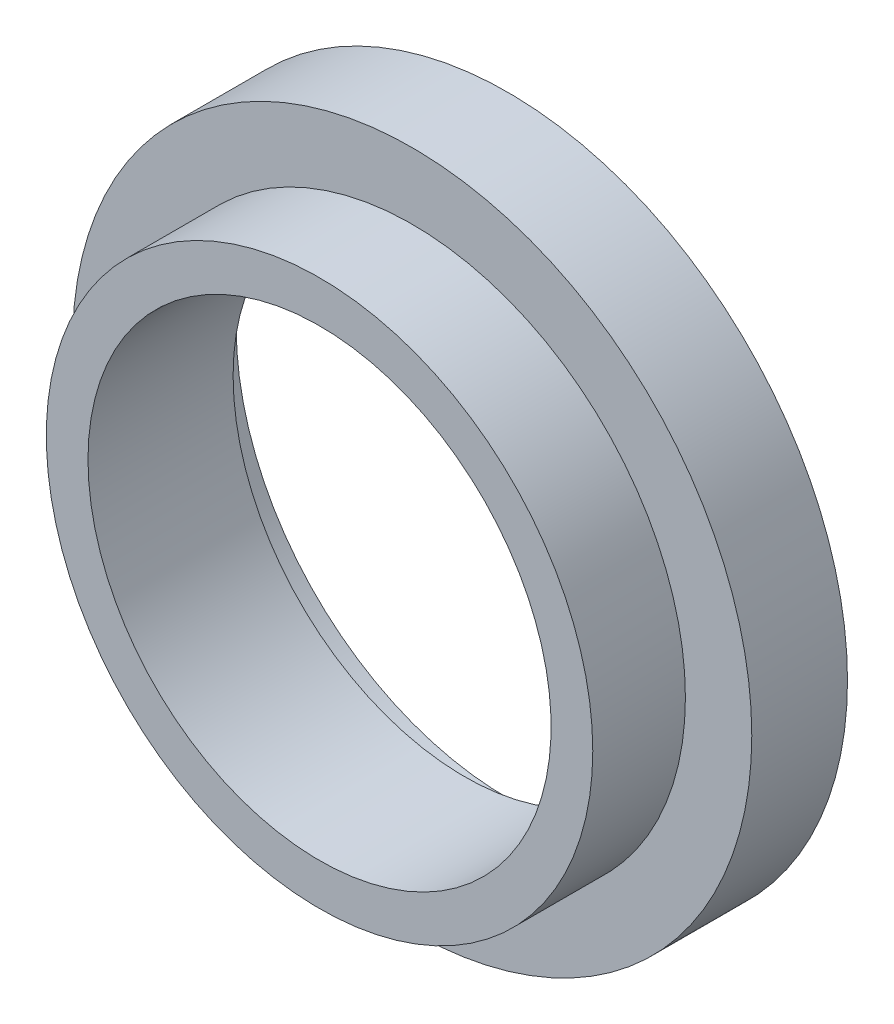
SolidWorks part; units mm, degrees
material "Phosphor bronze 10% D, UNS C52400"
ref_plane "Front Plane" through (0, 0, 0) normal (0, 0, 1) x (1, 0, 0)
ref_plane "Top Plane" through (0, 0, 0) normal (0, 1, 0) x (1, 0, 0)
ref_plane "Right Plane" through (0, 0, 0) normal (1, 0, 0) x (0, 0, -1)
sketch "Sketch1" plane through (0, 0, 0) normal (0, 0, 1) x (1, 0, 0)
  circle A0 centre (0, 0) radius 55
  dimension "D1" = 110
extrude "Boss-Extrude1" add sketch "Sketch1" along normal blind 15.5
sketch "Sketch2" plane through (0, 0, 15.5) normal (0, 0, 1) x (1, 0, 0)
  circle A0 centre (0, 0) radius 44.25
  dimension "D1" = 88.5
extrude "Boss-Extrude2" add sketch "Sketch2" along normal blind 15
sketch "Sketch3" plane through (0, 0, 0) normal (0, 0, -1) x (-1, 0, 0)
  circle A0 centre (0, 0) radius 44
  dimension "D1" = 88
extrude "Cut-Extrude1" cut sketch "Sketch3" against normal blind 7
sketch "Sketch4" plane through (0, 0, 7) normal (0, 0, -1) x (-1, 0, 0)
  circle A0 centre (0, 0) radius 37.5
  dimension "D1" = 75
extrude "Cut-Extrude2" cut sketch "Sketch4" against normal through all both and the other way through all
